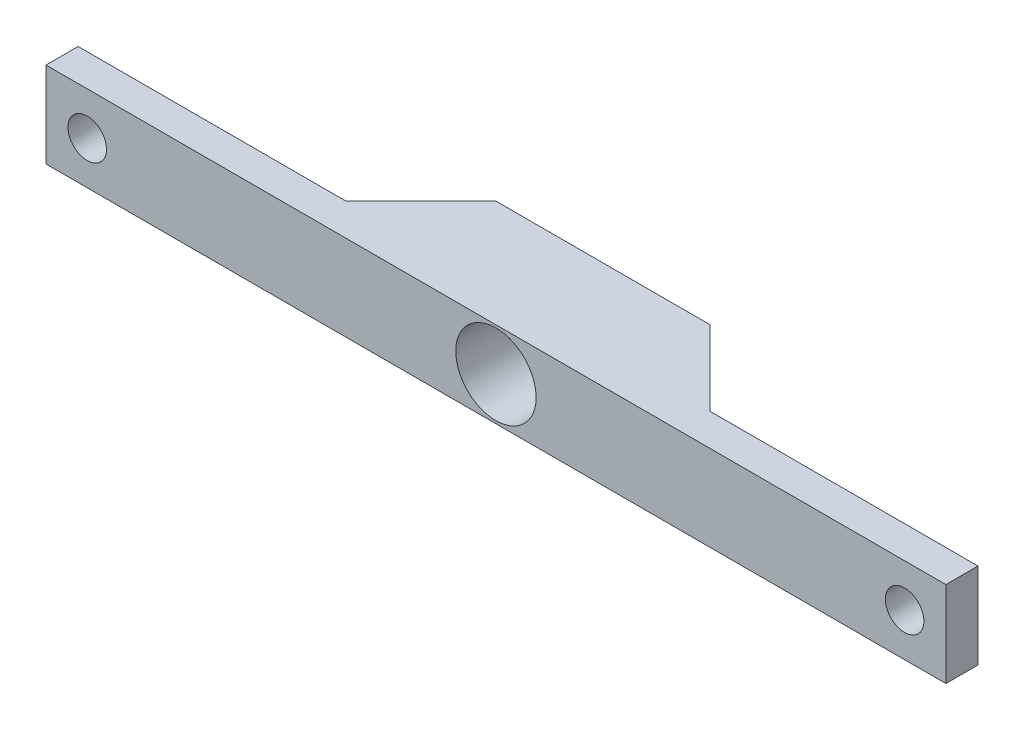
SolidWorks part; units mm, degrees
ref_plane "Front Plane" through (0, 0, 0) normal (0, 0, 1) x (1, 0, 0)
ref_plane "Top Plane" through (0, 0, 0) normal (0, 1, 0) x (1, 0, 0)
ref_plane "Right Plane" through (0, 0, 0) normal (1, 0, 0) x (0, 0, -1)
sketch "Sketch2" plane through (0, 0, 0) normal (0, 1, 0) x (1, 0, 0)
  line L0 (-10, 0) -> (10, 0)
  line L1 (10, 0) -> (20, -10)
  line L2 (20, -10) -> (-20, -10)
  line L3 (-20, -10) -> (-10, 0)
  point P4 (0, 0)
  dimension "D1" = 20
  dimension "D2" = 45
  dimension "D3" = 45
  dimension "D4" = 10
extrude "Boss-Extrude1" add sketch "Sketch2" along normal blind 8
sketch "Sketch3" plane through (0, 0, 10) normal (0, 0, 1) x (1, 0, 0)
  line L0 (-20, 0) -> (20, 0) construction
  line L1 (-42, 0) -> (42, 0)
  line L2 (-42, 0) -> (-42, 8)
  line L3 (-42, 8) -> (42, 8)
  line L4 (42, 0) -> (42, 8)
  line L5 (-42, 0) -> (42, 8) construction
  line L6 (-42, 8) -> (42, 0) construction
  point P0 (0, 4)
  point P5 (0, 0)
  dimension "D1" = 84
  dimension "D2" = 8
extrude "Boss-Extrude3" add sketch "Sketch3" against normal blind 3
sketch "Sketch4" plane through (0, 0, 10) normal (0, 0, 1) x (1, 0, 0)
  line L0 (-42, 8) -> (-42, 0) construction
  circle A0 centre (-38.15, 4) radius 1.8
  circle A1 centre (38.15, 4) radius 1.8
  point P6 (0, 0)
  point P7 (0, 0)
  point P9 (0, 0)
  point P12 (-42, 4)
  point P13 (0, 0)
  dimension "D1" = 38.15
  dimension "D3" = 3.6
  dimension "D2" = 38.15
extrude "Cut-Extrude1" cut sketch "Sketch4" against normal through all
sketch "Sketch5" plane through (0, 0, 0) normal (0, 0, -1) x (-1, 0, 0)
  line L0 (-42, 0) -> (-42, 8) construction
  circle A0 centre (0, 4) radius 1.8
  point P2 (0, 0)
  point P5 (-42, 4)
  point P6 (0, 0)
  dimension "D1" = 3.6
extrude "Cut-Extrude2" cut sketch "Sketch5" against normal through all
sketch "Sketch6" plane through (0, 0, 10) normal (0, 0, 1) x (1, 0, 0)
  circle A0 centre (0, 4) radius 3.75
  dimension "D1" = 7.5
extrude "Cut-Extrude3" cut sketch "Sketch6" against normal blind 6
